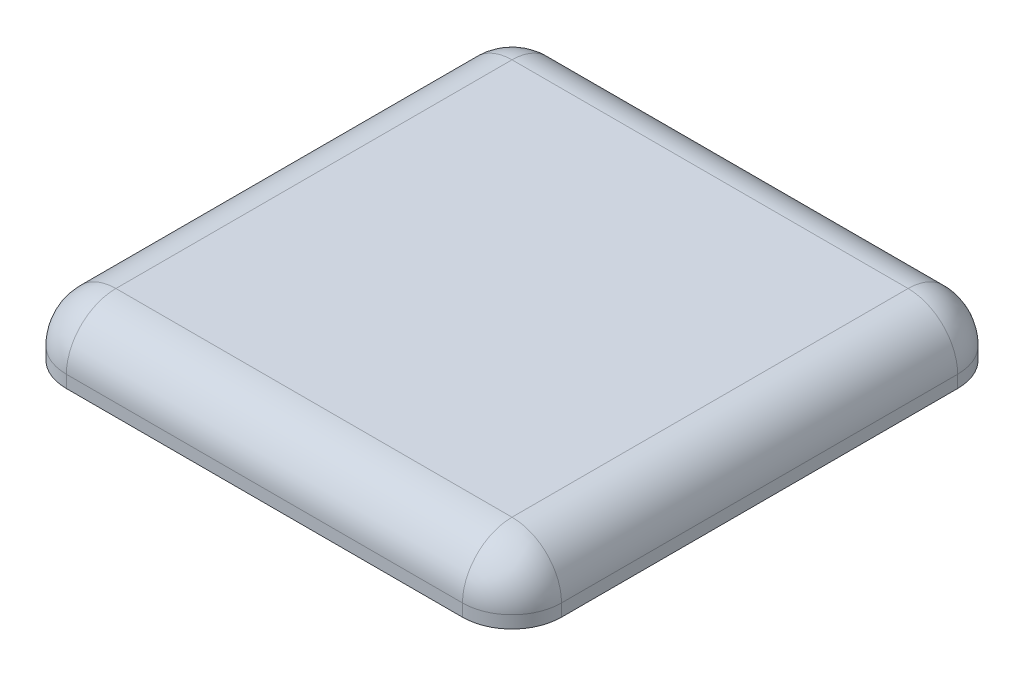
SolidWorks part; units mm, degrees
material "ABS"
ref_plane "Front Plane" through (0, 0, 0) normal (0, 0, 1) x (1, 0, 0)
ref_plane "Top Plane" through (0, 0, 0) normal (0, 1, 0) x (1, 0, 0)
ref_plane "Right Plane" through (0, 0, 0) normal (1, 0, 0) x (0, 0, -1)
ref_plane "Plane1" through (0, 2.5, 0) normal (0, 1, 0) x (1, 0, 0)
sketch "Sketch1" plane through (0, 2.5, 0) normal (0, 1, 0) x (1, 0, 0)
  line L0 (10, 10) -> (-10, 10)
  line L1 (-10, 10) -> (-10, -10)
  line L2 (-10, -10) -> (10, -10)
  line L3 (10, -10) -> (10, 10)
extrude "Boss-Extrude1" add sketch "Sketch1" against normal blind 2.5
sketch "Sketch2" plane through (0, 0, 0) normal (0, -1, 0) x (1, 0, 0)
  line L0 (-2.0156, 1) -> (-1, 1)
  line L1 (-1, 1) -> (-1, 2.0156)
  line L2 (1, 2.0156) -> (1, 1)
  line L3 (1, 1) -> (2.0156, 1)
  line L4 (2.0156, -1) -> (1, -1)
  line L5 (1, -1) -> (1, -2.0156)
  line L6 (-1, -2.0156) -> (-1, -1)
  line L7 (-1, -1) -> (-2.0156, -1)
  arc A0 (-2.0156, -1) -> (-2.0156, 1) centre (0, 0) cw
  arc A1 (-1, 2.0156) -> (1, 2.0156) centre (0, 0) cw
  arc A2 (2.0156, 1) -> (2.0156, -1) centre (0, 0) cw
  arc A3 (1, -2.0156) -> (-1, -2.0156) centre (0, 0) cw
extrude "Boss-Extrude2" add sketch "Sketch2" along normal blind 6
sketch "Sketch3" plane through (0, 0, 0) normal (0, -1, 0) x (1, 0, 0)
  line L0 (-9.5, -2.5) -> (-9.5, 2.5)
  line L1 (-9.5, 2.5) -> (-7.5, 2.5)
  line L2 (-7.5, 2.5) -> (-7.5, -2.5)
  line L3 (-7.5, -2.5) -> (-9.5, -2.5)
extrude "Boss-Extrude3" add sketch "Sketch3" along normal blind 3
fillet "Fillet1" radius 2 8 edges at (-10, 1.25, -10) (10, 1.25, -10) (0, 2.5, -10) (-10, 2.5, 0) (-10, 1.25, 10) (10, 2.5, 0) (0, 2.5, 10) (10, 1.25, 10)
